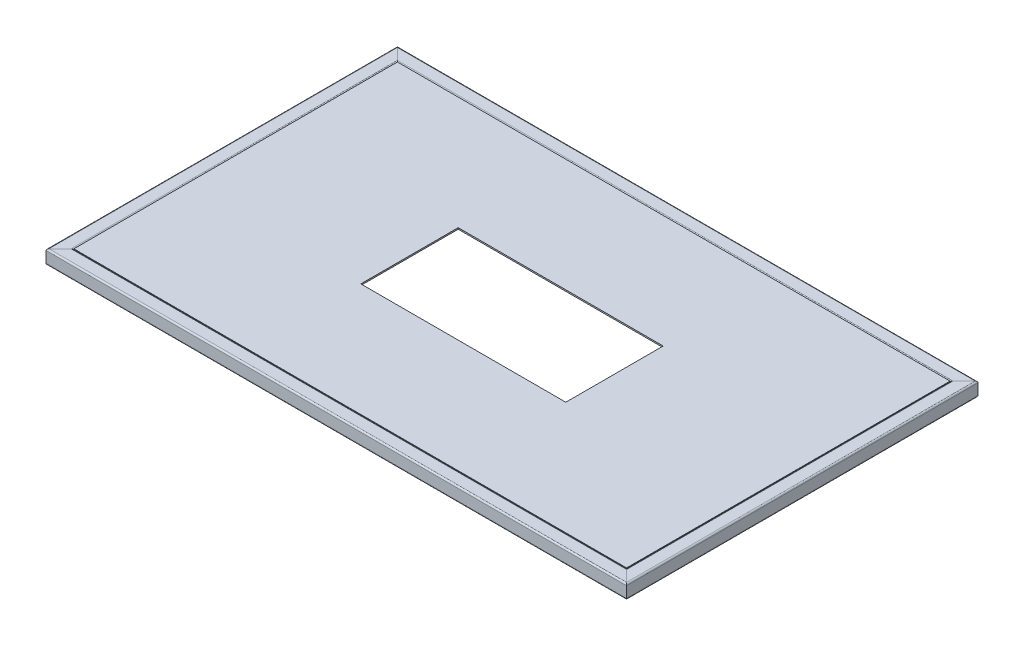
SolidWorks part; units mm, degrees
ref_plane "Alzado" through (0, 0, 0) normal (0, 0, 1) x (1, 0, 0)
ref_plane "Planta" through (0, 0, 0) normal (0, 1, 0) x (1, 0, 0)
ref_plane "Vista lateral" through (0, 0, 0) normal (1, 0, 0) x (0, 0, -1)
sketch "Croquis1" plane through (0, 0, 0) normal (0, 1, 0) x (1, 0, 0)
  line L1 (-396.5, 240) -> (396.5, 240)
  line L2 (-396.5, 240) -> (-396.5, -240)
  line L3 (-396.5, -240) -> (396.5, -240)
  line L4 (396.5, 240) -> (396.5, -240)
  line L5 (-396.5, 240) -> (396.5, -240) construction
  line L6 (-396.5, -240) -> (396.5, 240) construction
  point P0 (0, 0)
  dimension "D1" = 793
  dimension "D2" = 480
other "Tubo cuadrado 2 X 2 X 0.25(1)"
ref_plane "Plano1" through (-386.975, 9.525, -240) normal (0, 0, 1) x (1, 0, 0)
sketch "Sketch1" plane through (-386.975, 9.525, -240) normal (0, 0, 1) x (1, 0, 0)
  line L0 (-7.525, -8.525) -> (7.525, -8.525)
  line L1 (-8.525, -7.525) -> (-8.525, 7.525)
  line L2 (7.525, 8.525) -> (-7.525, 8.525)
  line L3 (8.525, 7.525) -> (8.525, -7.525)
  line L4 (-7.525, -9.525) -> (7.525, -9.525)
  line L5 (-9.525, -7.525) -> (-9.525, 7.525)
  line L6 (7.525, 9.525) -> (-7.525, 9.525)
  line L7 (9.525, 7.525) -> (9.525, -7.525)
  line L8 (0, 0) -> (8.525, 0) construction
  line L9 (0, 0) -> (0, 8.525) construction
  arc A0 (9.525, 7.525) -> (7.525, 9.525) centre (7.525, 7.525) ccw
  arc A1 (7.525, -9.525) -> (9.525, -7.525) centre (7.525, -7.525) ccw
  arc A2 (-9.525, -7.525) -> (-7.525, -9.525) centre (-7.525, -7.525) ccw
  arc A3 (-7.525, 9.525) -> (-9.525, 7.525) centre (-7.525, 7.525) ccw
  arc A4 (-7.525, 8.525) -> (-8.525, 7.525) centre (-7.525, 7.525) ccw
  arc A5 (8.525, 7.525) -> (7.525, 8.525) centre (7.525, 7.525) ccw
  arc A6 (7.525, -8.525) -> (8.525, -7.525) centre (7.525, -7.525) ccw
  arc A7 (-8.525, -7.525) -> (-7.525, -8.525) centre (-7.525, -7.525) ccw
  point P3 (0, 9.525)
  point P4 (9.525, 0)
  point P5 (0, -9.525)
  point P6 (-9.525, 0)
  point P7 (-9.525, 9.525)
  point P8 (-9.525, -9.525)
  point P33 (0, 0)
  point P35 (9.525, -9.525)
  point P36 (9.525, 9.525)
  point P37 (0, 0)
  dimension "D1" = 2
  dimension "Thickness" = 1
  dimension "V_leg" = 19.05
sketch "Croquis2" plane through (0, 19.05, 0) normal (0, 1, 0) x (1, 0, 0)
  line L1 (-377.45, -220.95) -> (377.45, -220.95)
  line L2 (-377.45, -220.95) -> (-377.45, 220.95)
  line L3 (-377.45, 220.95) -> (377.45, 220.95)
  line L4 (377.45, -220.95) -> (377.45, 220.95)
  line L5 (-377.45, -220.95) -> (377.45, 220.95) construction
  line L6 (-377.45, 220.95) -> (377.45, -220.95) construction
  point P0 (0, 0)
extrude "Saliente-Extruir1" add sketch "Croquis2" against normal blind 12.7 separate body
shell "Vaciado1" thickness 1.9
sketch "Croquis3" plane through (0, 17.15, 0) normal (0, -1, 0) x (-1, 0, 0)
  line L1 (-140, 66.5) -> (140, 66.5)
  line L2 (140, 66.5) -> (140, -66.5)
  line L3 (140, -66.5) -> (-140, -66.5)
  line L4 (-140, -66.5) -> (-140, 66.5)
extrude "Cortar-Extruir1" cut sketch "Croquis3" against normal blind 10
